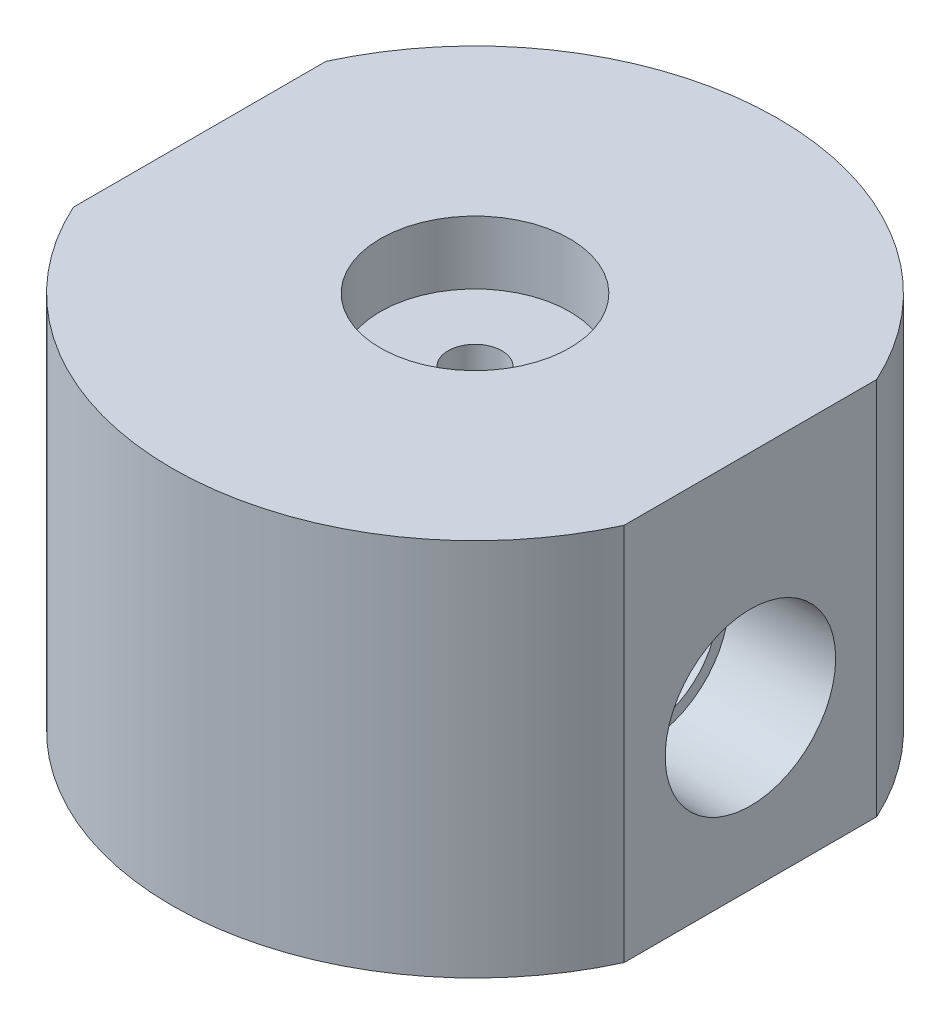
SolidWorks part; units mm, degrees
material "AISI Type 316L stainless steel"
ref_plane "Front Plane" through (0, 0, 0) normal (0, 0, 1) x (1, 0, 0)
ref_plane "Top Plane" through (0, 0, 0) normal (0, 1, 0) x (1, 0, 0)
ref_plane "Right Plane" through (0, 0, 0) normal (1, 0, 0) x (0, 0, -1)
sketch "Sketch1" plane through (0, 0, 0) normal (0, 0, 1) x (1, 0, 0)
  line L0 (0, 0) -> (0, 38.1) construction
  line L1 (0, 38.1) -> (-30.48, 38.1)
  line L2 (-30.48, 38.1) -> (-30.48, 0)
  line L3 (-30.48, 0) -> (-12.7, 0)
  line L4 (-12.7, 0) -> (-12.7, 25.4)
  line L5 (-12.7, 25.4) -> (-9.525, 25.4)
  line L6 (-4.7625, 20.6375) -> (0, 20.6375)
  line L7 (0, 38.1) -> (0, 20.6375)
  arc A0 (-9.525, 25.4) -> (-4.7625, 20.6375) centre (-9.525, 20.6375) cw
  dimension "D1" = 25.4
  dimension "D2" = 12.7
  dimension "D3" = 60.96
  dimension "D4" = 25.4
  dimension "D5" = 9.525
  dimension "D6" = 3.175
revolve "Revolve1" add sketch "Sketch1" angle 360 about L0
hole_wizard "1/4-28 Tapped Hole1" positions "Sketch2" profile "Sketch3" tap size "1/4-28" standard "ANSI Inch" end condition through all
sketch "Sketch2" plane through (0, 38.1, 0) normal (0, 1, 0) x (1, 0, 0)
  point P0 (0, 0)
sketch "Sketch3" plane through (0, 38.1, 0) normal (1, 0, 0) x (0, 0, 1)
  line L0 (0, 0) -> (0, 38.1)
  line L1 (0, 38.1) -> (2.7051, 38.1)
  line L2 (2.7051, 38.1) -> (2.7051, 0)
  line L5 (2.7051, 0) -> (0, 0)
  line L11 (0, -6.35) -> (0, 107.95) construction
  dimension "Thru Tap Drill Dia." = 5.4102
  dimension "Thru Tap Drill Depth" = 38.1
cosmetic thread "Hole Thread1" parameters "D2"=6.35
sketch "Sketch4" plane through (0, 0, 0) normal (0, 1, 0) x (1, 0, 0)
  line L0 (0, 0) -> (0, 17.6947) construction
  line L1 (-27.7081, 12.7) -> (-53.1081, 12.7)
  line L2 (-27.7081, 12.7) -> (-27.7081, -12.7)
  line L3 (-27.7081, -12.7) -> (-53.1081, -12.7)
  line L4 (-53.1081, 12.7) -> (-53.1081, -12.7)
  line L5 (53.1081, 12.7) -> (53.1081, -12.7)
  line L6 (27.7081, -12.7) -> (53.1081, -12.7)
  line L7 (27.7081, 12.7) -> (27.7081, -12.7)
  line L8 (27.7081, 12.7) -> (53.1081, 12.7)
  circle A0 centre (0, 0) radius 30.48 construction
  dimension "D1" = 25.4
extrude "flats" cut sketch "Sketch4" along normal through all
hole_wizard "3/8 NPT Tapped Hole1" positions "Sketch5" profile "Sketch6" size "3/8" standard "ANSI Inch"
sketch "Sketch5" plane through (27.7081, 0, 0) normal (1, 0, 0) x (0, 0, -1)
  line L0 (-12.7, 25.4) -> (12.7, 25.4) construction
  line L1 (-12.7, 38.1) -> (-12.7, 0) construction
  line L2 (12.7, 38.1) -> (12.7, 0) construction
  line L4 (-12.7, 25.4) -> (12.7, 25.4) construction
  line L6 (0, 25.4) -> (0, 15.875) construction
  point P0 (0, 15.875)
  point P25 (0, 16.0505)
  point P26 (0, 0)
  point P27 (0, 0)
  point P28 (0, 17.0633)
  dimension "D1" = 9.525
sketch "Sketch6" plane through (27.7081, 15.875, 0) normal (0, 1, 0) x (0, 0, -1)
  line L0 (0, 0) -> (0, 21.8146)
  line L1 (7.1374, 17.526) -> (0, 21.8146)
  line L2 (-7.1374, 17.526) -> (0, 21.8146) construction
  line L3 (7.1374, 17.526) -> (7.1374, 10.414)
  line L4 (7.1374, 10.414) -> (8.2632, 10.414)
  line L5 (8.2632, 10.414) -> (8.575, 0)
  line L6 (-8.2632, 10.414) -> (-8.575, 0) construction
  line L7 (8.575, 0) -> (0, 0)
  line L8 (0, -6.35) -> (0, 107.95) construction
  line L11 (-7.1374, 10.414) -> (-8.2632, 10.414) construction
  dimension "Tap Drill Dia." = 14.2748
  dimension "Tap Drill Depth" = 17.526
  dimension "Thread Dia." = 17.15
  dimension "Thread Angle" = 3.43
  dimension "Thread Depth" = 10.414
  dimension "Drill Angle" = 118
mirror "Mirror1" about plane through (0, 0, 0) normal (1, 0, 0) of "3/8 NPT Tapped Hole1"
fillet "Fillet1" radius 1.5875 1 edges at (12.7, 25.4, 0)
sketch "Sketch7" plane through (0, 38.1, 0) normal (0, 1, 0) x (1, 0, 0)
  circle A0 centre (0, 0) radius 9.525
  dimension "D1" = 19.05
extrude "Cut-Extrude1" cut sketch "Sketch7" against normal blind 6.35
